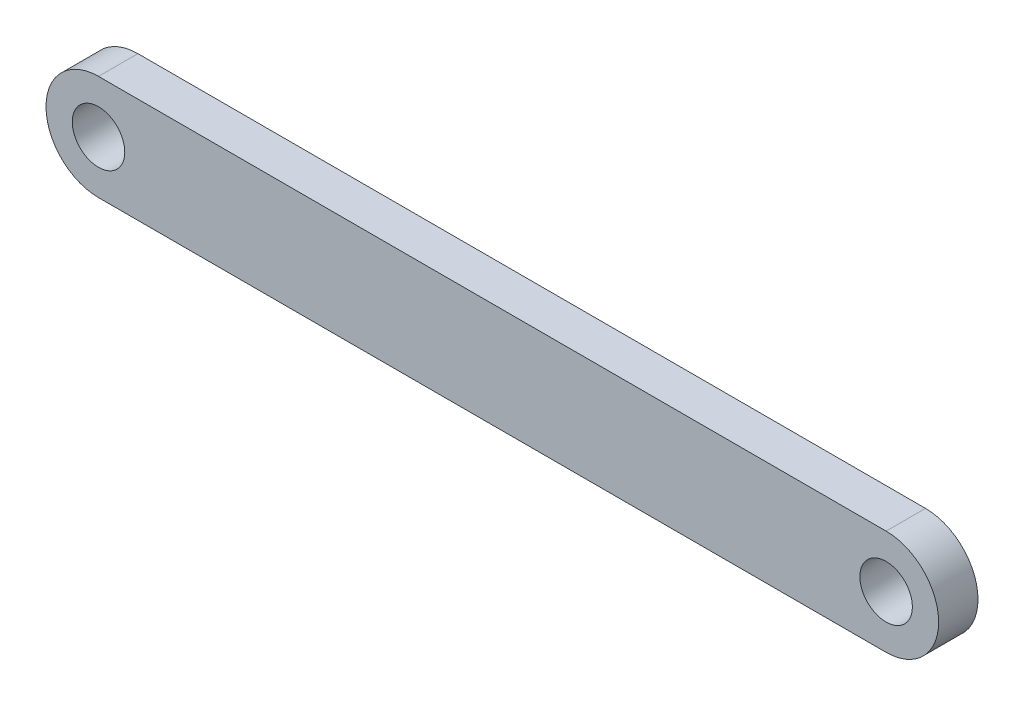
SolidWorks part; units mm, degrees
material "Zoltek Panex 33"
ref_plane "前视基准面" through (0, 0, 0) normal (0, 0, 1) x (1, 0, 0)
ref_plane "上视基准面" through (0, 0, 0) normal (0, 1, 0) x (1, 0, 0)
ref_plane "右视基准面" through (0, 0, 0) normal (1, 0, 0) x (0, 0, -1)
sketch "草图1" plane through (0, 0, 0) normal (0, 0, 1) x (1, 0, 0)
  line L1 (0, 0) -> (30, 0) construction
  line L2 (0, 2) -> (30, 2)
  line L3 (0, -2) -> (30, -2)
  arc A1 (0, 2) -> (0, -2) centre (0, 0) ccw
  arc A2 (30, -2) -> (30, 2) centre (30, 0) ccw
  circle A3 centre (30, 0) radius 1
  circle A4 centre (0, 0) radius 1
  point P6 (15, 0)
  dimension "D1" = 2
  dimension "D3" = 2
  dimension "D4" = 2
  dimension "D2" = 30
extrude "凸台-拉伸1" add sketch "草图1" along normal blind 1.5
